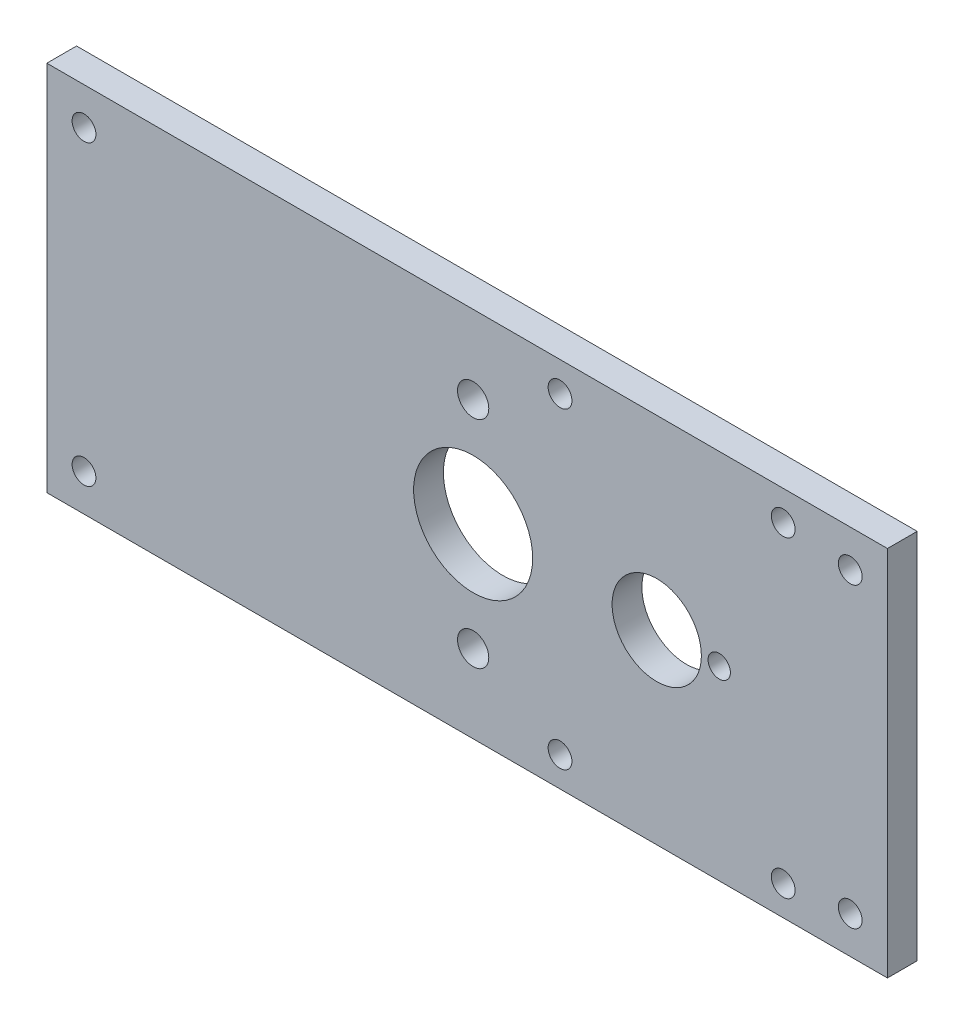
SolidWorks part; units mm, degrees
ref_plane "正面" through (0, 0, 0) normal (0, 0, 1) x (1, 0, 0)
ref_plane "平面" through (0, 0, 0) normal (0, 1, 0) x (1, 0, 0)
ref_plane "右側面" through (0, 0, 0) normal (1, 0, 0) x (0, 0, -1)
sketch "ｽｹｯﾁ1" plane through (0, 0, 0) normal (0, 0, 1) x (1, 0, 0)
  line L1 (0, 0) -> (113, 0)
  line L2 (0, 0) -> (0, 50)
  line L3 (0, 50) -> (113, 50)
  line L4 (113, 0) -> (113, 50)
  circle A0 centre (5, 45) radius 1.6
  circle A1 centre (5, 5) radius 1.6
  circle A2 centre (108, 45) radius 1.6
  circle A3 centre (108, 5) radius 1.6
  circle A4 centre (57.31, 25) radius 8
  circle A6 centre (81.99, 25) radius 6
  point P17 (113, 25)
  dimension "D1" = 5
  dimension "D2" = 5
  dimension "D3" = 5
  dimension "D4" = 5
  dimension "D6" = 5
  dimension "D7" = 5
  dimension "D8" = 5
  dimension "D9" = 3.2
  dimension "D10" = 3.2
  dimension "D11" = 3.2
  dimension "D12" = 3.2
  dimension "D15" = 16
  dimension "D16" = 31.01
  dimension "D17" = 25
  dimension "D18" = 0
  dimension "D19" = 12
  dimension "D20" = 24.68
  dimension "D5" = 5
  dimension "D13" = 50
  dimension "D14" = 113
extrude "ﾎﾞｽ - 押し出し1" add sketch "ｽｹｯﾁ1" along normal blind 4
sketch "ｽｹｯﾁ2" plane through (0, 0, 4) normal (0, 0, 1) x (1, 0, 0)
  line L0 (113, 0) -> (113, 50) construction
  line L1 (68.99, 46) -> (98.99, 46)
  line L2 (68.99, 46) -> (68.99, 4)
  line L3 (68.99, 4) -> (98.99, 4)
  line L4 (98.99, 46) -> (98.99, 4)
  line L5 (68.99, 46) -> (98.99, 4) construction
  line L6 (68.99, 4) -> (98.99, 46) construction
  line L7 (0, 0) -> (113, 0) construction
  line L8 (113, 50) -> (0, 50) construction
  circle A0 centre (57.31, 39.5) radius 2.1
  circle A1 centre (57.31, 10.5) radius 2.1
  circle A2 centre (57.31, 25) radius 8 construction
  circle A3 centre (57.31, 25) radius 8 construction
  circle A4 centre (81.99, 25) radius 6 construction
  circle A5 centre (98.99, 46) radius 1.6
  circle A6 centre (68.99, 46) radius 1.6
  circle A7 centre (68.99, 4) radius 1.6
  circle A8 centre (98.99, 4) radius 1.6
  circle A9 centre (90.39, 25) radius 1.5
  circle A10 centre (81.99, 25) radius 6 construction
  circle A11 centre (43, 5) radius 1.6
  circle A12 centre (43, 45) radius 1.6
  point P8 (83.99, 25)
  dimension "D1" = 4.2
  dimension "D2" = 4.2
  dimension "D3" = 14.5
  dimension "D4" = 14.5
  dimension "D5" = 0
  dimension "D6" = 0
  dimension "D10" = 2
  dimension "D11" = 3.2
  dimension "D12" = 3.2
  dimension "D13" = 3.2
  dimension "D14" = 3.2
  dimension "D15" = 3
  dimension "D16" = 8.4
  dimension "D17" = 0
  dimension "D18" = 3.2
  dimension "D19" = 3.2
  dimension "D20" = 70
  dimension "D21" = 70
  dimension "D22" = 5
  dimension "D23" = 5
  dimension "D7" = 42
  dimension "D8" = 30
  dimension "D9" = 0
extrude "ｶｯﾄ - 押し出し1" cut sketch "ｽｹｯﾁ2" against normal through all contours A9 | A5 | A8 | A7 | A6 | A0 | A1
sketch "ｽｹｯﾁ3" plane through (0, 0, 4) normal (0, 0, 1) x (1, 0, 0)
  line L0 (5, 45) -> (57.31, 25) construction
  line L1 (57.31, 25) -> (5, 5) construction
  line L2 (5, 5) -> (108, 45) construction
  line L3 (108, 45) -> (108, 5) construction
  line L4 (5, 45) -> (108, 5) construction
  line L5 (10, 38.8059) -> (10, 11.1941)
  line L6 (10, 11.1941) -> (39.4889, 22.4687)
  line L7 (10, 38.8059) -> (39.4889, 27.5313)
  line L8 (103, 36.1095) -> (103, 13.8905)
  line L9 (108, 5) -> (81.99, 25) construction
  line L10 (103, 36.1095) -> (92.5514, 28.0752)
  line L11 (0, 50) -> (0, 0) construction
  line L12 (113, 0) -> (113, 50) construction
  line L13 (81.99, 25) -> (108, 45) construction
  line L14 (103, 13.8905) -> (92.5514, 21.9248)
  line L16 (103, 22) -> (10, 22)
  line L17 (103, 22) -> (103, 28)
  line L18 (103, 28) -> (10, 28)
  line L19 (10, 22) -> (10, 28)
  line L20 (103, 22) -> (10, 28) construction
  line L21 (103, 28) -> (10, 22) construction
  circle A0 centre (57.31, 25) radius 18
  circle A1 centre (81.99, 25) radius 11
  circle A2 centre (81.99, 25) radius 6 construction
  circle A3 centre (57.31, 25) radius 8 construction
  point P30 (56.5, 25)
  dimension "D7" = 5
  dimension "D8" = 10
  dimension "D1" = 4
  dimension "D2" = 4
  dimension "D3" = 10
  dimension "D4" = 10
  dimension "D5" = 4
  dimension "D6" = 4
  dimension "D9" = 6
